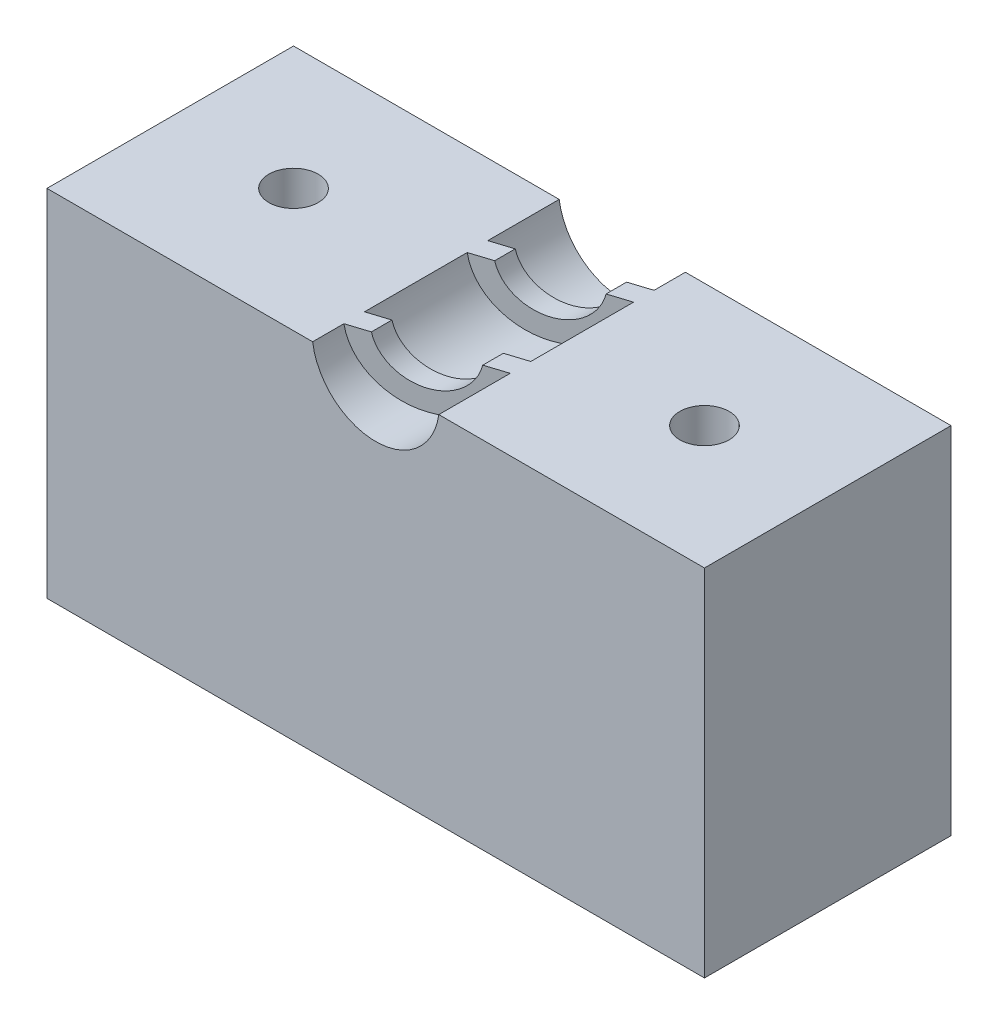
SolidWorks part; units mm, degrees
ref_plane "前视基准面" through (0, 0, 0) normal (0, 0, 1) x (1, 0, 0)
ref_plane "上视基准面" through (0, 0, 0) normal (0, 1, 0) x (1, 0, 0)
ref_plane "右视基准面" through (0, 0, 0) normal (1, 0, 0) x (0, 0, -1)
other "Configuration Table"
sketch "草图1" plane through (0, 0, 0) normal (0, 0, 1) x (1, 0, 0)
  line L1 (-8, -8) -> (8, -8)
  line L2 (-8, -8) -> (-8, 8)
  line L3 (-8, 8) -> (8, 8)
  line L4 (8, -8) -> (8, 8)
  line L5 (-8, -8) -> (8, 8) construction
  line L6 (-8, 8) -> (8, -8) construction
  circle A0 centre (0, 0) radius 1.55
  point P0 (0, 0)
  dimension "D3" = 3.1
  dimension "D1" = 16
  dimension "D2" = 16
extrude "凸台-拉伸1" add sketch "草图1" along normal mid plane 6
sketch "草图6" plane through (0, 0, 0) normal (0, 1, 0) x (1, 0, 0)
  line L0 (-1.55, -3) -> (1.55, -3) construction
  line L1 (1.55, 3) -> (-1.55, 3) construction
  line L2 (-1.55, -3) -> (1.55, -3)
  line L3 (1.55, 3) -> (-1.55, 3)
  line L4 (-1.55, 3) -> (-1.55, -3)
  line L5 (1.55, -3) -> (1.55, 3)
  line L6 (-1.55, 0.7565) -> (1.55, 1.7435)
  line L7 (1.55, 1.7435) -> (1.55, 2.2435)
  line L8 (1.55, 2.2435) -> (-1.55, 1.2565)
  line L9 (-1.55, -1.7435) -> (1.55, -0.7565)
  line L10 (-1.55, -2.2435) -> (1.55, -1.2565)
  line L11 (-2.0945, -0.6668) -> (3.135, 0.9981) construction
  line L12 (-3.1004, 0) -> (4.2723, 0) construction
  dimension "D1" = 2.5
  dimension "D2" = 0.5
  dimension "D3" = 0.5
  dimension "D4" = 17.66
extrude "凸台-拉伸2" add sketch "草图6" against normal up to surface (8 mm away) contours L4 L10 L5 L9 | L5 L8 L4 L6 up to face at (0, -8, 0)
sketch "草图7" plane through (0, 0, 0) normal (0, 0, 1) x (1, 0, 0)
  line L0 (0, 0) -> (-1.0279, -0.2141)
  line L1 (0, 0) -> (1.0279, -0.2141)
  line L2 (-1.0279, -0.2141) -> (-8, -0.2141)
  line L3 (1.0279, -0.2141) -> (8, -0.2141)
  line L6 (8, -8) -> (8, 8)
  line L7 (-8, -8) -> (8, -8)
  line L8 (-8, 8) -> (-8, -8)
  line L9 (8, 8) -> (-8, 8)
  line L10 (8, -8) -> (8, 8)
  line L11 (-8, -8) -> (8, -8)
  line L12 (-8, 8) -> (-8, -8)
  line L13 (8, 8) -> (-8, 8)
  circle A0 centre (0, 0) radius 1.05
  dimension "D1" = 2.1
  dimension "D2" = 0
  dimension "D3" = 156.47
extrude "切除-拉伸2" cut sketch "草图7" against normal through all both and the other way through all contours A0 L3 L10 L13 L12 L2 | L1 A0 L0 | L0 A0 L1
sketch "草图8" plane through (0, 0, 0) normal (0, 1, 0) x (1, 0, 0)
  line L0 (0, 5.5834) -> (0, -5.0797) construction
  circle A0 centre (-5, 0) radius 0.6
  circle A1 centre (5, 0) radius 0.6
  dimension "D2" = 1.2
  dimension "D3" = 10
extrude "切除-拉伸3" cut sketch "草图8" against normal through all
sketch "草图9" plane through (0, -8, 0) normal (0, -1, 0) x (1, 0, 0)
  line L4 (-8, -3) -> (8, -3)
  line L5 (8, -3) -> (8, 3)
  line L6 (8, 3) -> (-8, 3)
  line L7 (-8, 3) -> (-8, -3)
  line L8 (-8, -3) -> (8, -3)
  line L9 (8, -3) -> (8, 3)
  line L10 (8, 3) -> (-8, 3)
  line L11 (-8, 3) -> (-8, -3)
  circle A0 centre (-5, 0) radius 0.6 construction
  circle A1 centre (5, 0) radius 0.6 construction
  circle A2 centre (-5, 0) radius 0.6
  circle A3 centre (5, 0) radius 0.6
  dimension "D1" = 0
extrude "凸台-拉伸3" add sketch "草图9" along normal offset from surface (0.855 mm away) 0.1
equation "\"x\"=0.8094"
